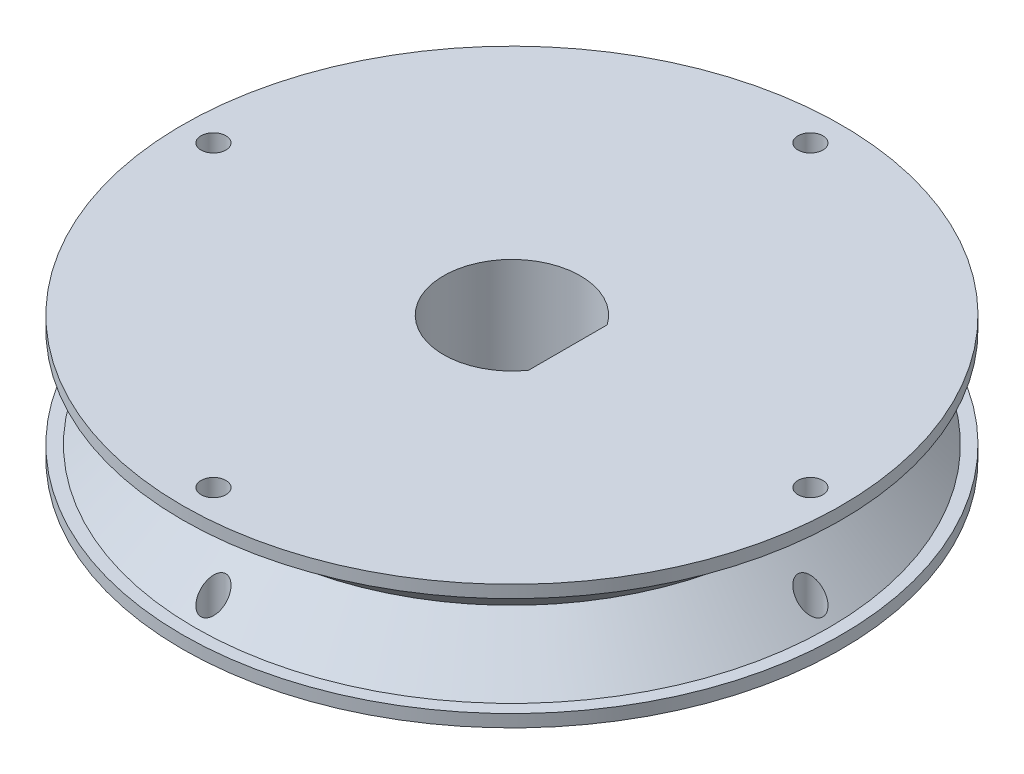
SolidWorks part; units mm, degrees
ref_plane "Front Plane" through (0, 0, 0) normal (0, 0, 1) x (1, 0, 0)
ref_plane "Top Plane" through (0, 0, 0) normal (0, 1, 0) x (1, 0, 0)
ref_plane "Right Plane" through (0, 0, 0) normal (1, 0, 0) x (0, 0, -1)
sketch "Sketch1" plane through (0, 0, 0) normal (0, 1, 0) x (1, 0, 0)
  line L0 (2, 1.5) -> (2, -1.5) construction
  line L1 (2.25, 1.5811) -> (2.25, -1.5811)
  arc A0 (2, 1.5) -> (2, -1.5) centre (0, 0) ccw construction
  arc A1 (2.25, 1.5811) -> (2.25, -1.5811) centre (0, 0) ccw
  circle A2 centre (0, 0) radius 13.25
  dimension "D1" = 5
  dimension "D3" = 0.25
  dimension "D4" = 5.5
  dimension "D2" = 2
extrude "Boss-Extrude1" add sketch "Sketch1" along normal blind 5
ref_plane "Plane1" through (0, 0, 0) normal (-1, 0, 0) x (0, 0, 1)
ref_axis "Axis2" through (0, 5, 0) along (0, -1, 0)
sketch "Sketch4" plane through (0, 0, 0) normal (-1, 0, 0) x (0, 0, 1)
  line L0 (12.75, 4.5) -> (10.75, 2.5)
  line L1 (10.75, 2.5) -> (12.75, 0.5)
  line L2 (13.25, 0) -> (13.25, 5) construction
  line L3 (13.25, 0) -> (13.25, 5) construction
  line L4 (13.25, 4.5) -> (13.25, 0.5)
  line L5 (12.75, 4.5) -> (13.25, 4.5)
  line L6 (13.25, 5) -> (-13.25, 5) construction
  line L7 (12.75, 0.5) -> (13.25, 0.5)
  line L8 (-13.25, 0) -> (13.25, 0) construction
  dimension "D1" = 45
  dimension "D2" = 45
  dimension "D3" = 0.5
  dimension "D4" = 0.5
revolve "Cut-Revolve1" cut sketch "Sketch4" angle 360 about axis through (0, 5, 0) along (0, -1, 0)
sketch "Sketch5" plane through (0, 5, 0) normal (0, 1, 0) x (1, 0, 0)
  line L0 (0, 0) -> (18.1073, 0) construction
  line L1 (0, 0) -> (-19.2579, 0) construction
  line L2 (0, 0) -> (0, 13.7804) construction
  line L3 (0, 0) -> (0, -15.0734) construction
  line L4 (0, 1.7393) -> (0, -1.7393) construction
  line L5 (0, 0) -> (-11.6243, -11.6243) construction
  circle A0 centre (-12, 0) radius 0.5
  circle A1 centre (12, 0) radius 0.5
  circle A2 centre (0, 12) radius 0.5
  circle A3 centre (0, -12) radius 0.5
  dimension "D1" = 12
extrude "Cut-Extrude1" cut sketch "Sketch5" against normal blind 5
